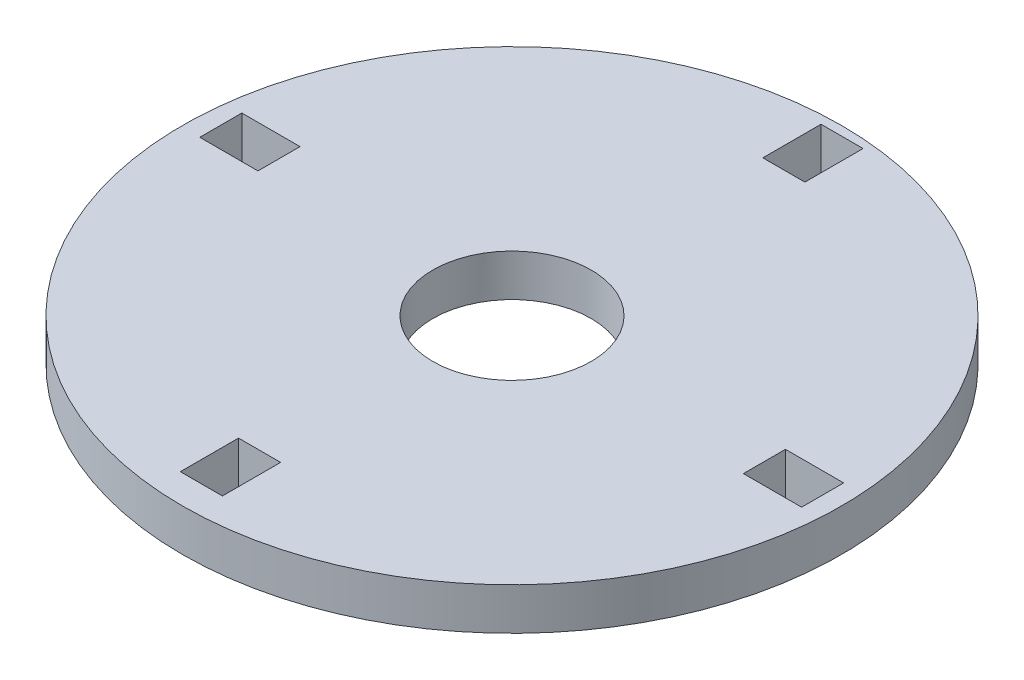
SolidWorks part; units mm, degrees
ref_plane "Přední rovina" through (0, 0, 0) normal (0, 0, 1) x (1, 0, 0)
ref_plane "Horní rovina" through (0, 0, 0) normal (0, 1, 0) x (1, 0, 0)
ref_plane "Pravá rovina" through (0, 0, 0) normal (1, 0, 0) x (0, 0, -1)
sketch "Skica1" plane through (0, 0, 0) normal (0, 1, 0) x (1, 0, 0)
  circle A0 centre (0, 0) radius 16.78
  dimension "D1" = 33.56
extrude "Přidat vysunutím1" add sketch "Skica1" along normal blind 50.7
sketch "Skica2" plane through (0, 50.7, 0) normal (0, 1, 0) x (1, 0, 0)
  circle A0 centre (0, 0) radius 5.65
  dimension "D1" = 11.3
extrude "Přidat vysunutím2" add sketch "Skica2" along normal blind 4.61
sketch "Skica3" plane through (0, 55.31, 0) normal (0, 1, 0) x (1, 0, 0)
  circle A0 centre (0, 0) radius 1.565
  dimension "D1" = 3.13
extrude "Přidat vysunutím3" add sketch "Skica3" along normal blind 8.5
sketch "Sketch6" plane through (0, 0, 0) normal (0, -1, 0) x (1, 0, 0)
  circle A0 centre (0, 0) radius 23.5
  dimension "D1" = 47
extrude "Boss-Extrude1" add sketch "Sketch6" along normal blind 3
sketch "Sketch8" plane through (0, 0, 0) normal (0, 1, 0) x (1, 0, 0)
  line L0 (-2.1926, -17.3074) -> (0.8074, -17.3074)
  line L1 (18, -1.5) -> (22.15, -1.5)
  line L2 (18, -1.5) -> (18, 1.5)
  line L3 (18, 1.5) -> (22.15, 1.5)
  line L4 (22.15, -1.5) -> (22.15, 1.5)
  line L5 (18, -1.5) -> (22.15, 1.5) construction
  line L6 (18, 1.5) -> (22.15, -1.5) construction
  line L7 (-2.1926, -17.3074) -> (-2.1926, -21.4574)
  line L8 (-2.1926, -21.4574) -> (0.8074, -21.4574)
  line L9 (0.8074, -17.3074) -> (0.8074, -21.4574)
  line L10 (-2.1926, -17.3074) -> (0.8074, -21.4574) construction
  line L11 (0.8074, -17.3074) -> (-2.1926, -21.4574) construction
  line L12 (-18, 2.8853) -> (-18, -0.1147)
  line L13 (-18, 2.8853) -> (-22.15, 2.8853)
  line L14 (-22.15, 2.8853) -> (-22.15, -0.1147)
  line L15 (-18, -0.1147) -> (-22.15, -0.1147)
  line L16 (-18, 2.8853) -> (-22.15, -0.1147) construction
  line L17 (-18, -0.1147) -> (-22.15, 2.8853) construction
  line L18 (2.1926, 18.6926) -> (-0.8074, 18.6926)
  line L19 (2.1926, 18.6926) -> (2.1926, 22.8426)
  line L20 (2.1926, 22.8426) -> (-0.8074, 22.8426)
  line L21 (-0.8074, 18.6926) -> (-0.8074, 22.8426)
  line L22 (2.1926, 18.6926) -> (-0.8074, 22.8426) construction
  line L23 (-0.8074, 18.6926) -> (2.1926, 22.8426) construction
  line L24 (0, 0) -> (32.2323, 0) construction
  circle A0 centre (0, 0) radius 16.78 construction
  point P0 (20.075, 0)
  point P10 (-0.6926, -19.3824)
  point P15 (-20.075, 1.3853)
  point P20 (0.6926, 20.7676)
  point P25 (0, 0.6926)
  dimension "D1" = 4.15
  dimension "D2" = 3
  dimension "D3" = 18
  dimension "D5" = 1.5
  dimension "D4" = 4
sketch "Skica4" plane through (0, 63.81, 0) normal (0, 1, 0) x (1, 0, 0)
  circle A0 centre (0, 0) radius 47.0258
  dimension "D1" = 94.0516
extrude "Odebrat vysunutím2" cut sketch "Skica4" against normal up to surface (63.81 mm away) up to face at (0, 0, 16.78)
sketch "Skica5" plane through (0, 0, 0) normal (0, 1, 0) x (1, 0, 0)
  circle A0 centre (0, 0) radius 5.65
  dimension "D1" = 11.3
extrude "Odebrat vysunutím3" cut sketch "Skica5" against normal blind 10
extrude "Odebrat vysunutím4" cut sketch "Sketch8" against normal blind 3
